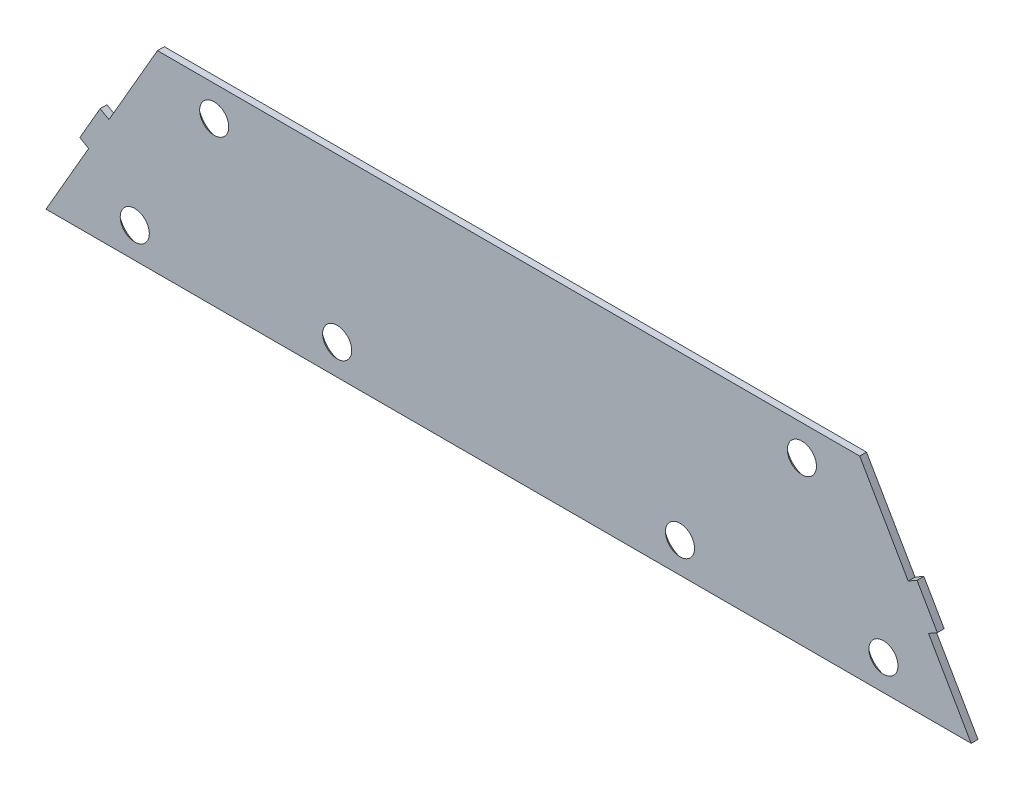
SolidWorks part; units mm, degrees
material "1023 Carbon Steel Sheet (SS)"
ref_plane "Front Plane" through (0, 0, 0) normal (0, 0, 1) x (1, 0, 0)
ref_plane "Top Plane" through (0, 0, 0) normal (0, 1, 0) x (1, 0, 0)
ref_plane "Right Plane" through (0, 0, 0) normal (1, 0, 0) x (0, 0, -1)
sketch "Sketch1" plane through (0, 0, 0) normal (0, 0, 1) x (1, 0, 0)
  line L0 (-55.1914, 13.7311) -> (-72.6057, -16.4314)
  line L1 (75.6033, -16.4314) -> (-72.6057, -16.4314)
  line L3 (58.189, 13.7311) -> (-55.1914, 13.7311)
  line L8 (58.189, 13.7311) -> (75.6033, -16.4314)
  point P0 (0, 0)
  dimension "D1" = 30.1625
  dimension "D2" = 148.209
  dimension "D3" = 60
  dimension "D4" = 60
extrude "Boss-Extrude1" add sketch "Sketch1" along normal blind 1.0668
ref_plane "Plane1" through (1.4988, 0, 0) normal (-1, 0, 0) x (0, 0, 1)
hole_wizard "CSK for #6 Flat Head Machine Screw (100)1" positions "Sketch3" profile "Sketch2" countersink size "#6" standard "ANSI Inch" end condition through all
sketch "Sketch3" plane through (0, 0, 0) normal (0, 0, -1) x (-1, 0, 0)
  circle A6 centre (-47.3288, 8.9686) radius 1.3525 construction
  circle A7 centre (-28.2788, -11.6689) radius 1.3525 construction
  circle A11 centre (44.4922, 8.9686) radius 1.3525 construction
  point P46 (-28.2788, -11.6689)
  point P55 (44.4922, 8.9686)
  point P61 (-47.3288, 8.9686)
  point P105 (-60.0628, -11.6689)
  point P111 (56.9042, -11.6689)
  point P118 (25.2812, -11.6689)
sketch "Sketch2" plane through (28.2788, -11.6689, 0) normal (1, 0, 0) x (0, 1, 0)
  line L0 (0, 0) -> (0, 1.0668)
  line L1 (0, 1.0668) -> (1.8986, 1.0668)
  line L2 (1.8986, 1.0668) -> (1.8986, 1.38)
  line L3 (1.8986, 1.38) -> (3.5433, 0)
  line L5 (3.5433, 0) -> (0, 0)
  line L6 (-1.8986, 1.38) -> (-3.5433, 0) construction
  line L11 (0, -6.35) -> (0, 107.95) construction
  dimension "Thru Hole Dia." = 3.7973
  dimension "Thru Hole Depth" = 1.0668
  dimension "Near C'Sink Dia." = 7.0866
  dimension "Near C'Sink Angle" = 100
sketch "Sketch4" plane through (0, 0, 0) normal (0, 0, -1) x (-1, 0, 0)
  line L0 (-75.6033, -16.4314) -> (-58.189, 13.7311) construction
  line L1 (-58.189, 13.7311) -> (55.1914, 13.7311) construction
  line L2 (72.6057, -16.4314) -> (-75.6033, -16.4314) construction
  line L4 (-65.3086, 1.3995) -> (-63.9338, 0.6057)
  line L5 (-58.189, 13.7311) -> (55.1914, 13.7311) construction
  line L6 (72.6057, -16.4314) -> (-75.6033, -16.4314) construction
  line L7 (-58.189, 13.7311) -> (55.1914, 13.7311) construction
  line L8 (-75.6033, -16.4314) -> (-58.189, 13.7311) construction
  line L9 (72.6057, -16.4314) -> (-75.6033, -16.4314) construction
  line L10 (-56.3559, 13.7311) -> (-58.189, 13.7311)
  line L11 (-56.3559, 13.7311) -> (-73.7702, -16.4314) construction
  line L12 (-58.189, 13.7311) -> (-65.3086, 1.3995)
  line L13 (-75.6033, -16.4314) -> (-58.189, 13.7311) construction
  line L14 (-63.9338, 0.6057) -> (-56.3559, 13.7311)
  line L15 (-63.9338, 0.6057) -> (-65.3086, 1.3995) construction
  line L16 (-65.3086, 1.3995) -> (-68.4836, -4.0998) construction
  line L17 (-68.4836, -4.0998) -> (-67.1088, -4.8936) construction
  line L18 (-67.1088, -4.8936) -> (-63.9338, 0.6057) construction
  line L19 (-66.8961, -1.3502) -> (-65.5213, -2.1439) construction
  line L20 (-68.4836, -4.0998) -> (-67.1088, -4.8936)
  line L21 (-67.1088, -4.8936) -> (-73.7702, -16.4314)
  line L22 (-73.7702, -16.4314) -> (-75.6033, -16.4314)
  line L23 (-75.6033, -16.4314) -> (-68.4836, -4.0998)
  line L24 (-68.4836, -4.0998) -> (-58.9851, -4.2071)
  point P16 (-65.5213, -2.1439)
  dimension "D1" = 1.5875
  dimension "D4" = 6.35
extrude "Cut-Extrude1" cut sketch "Sketch4" against normal through all
mirror "Mirror1" about plane through (1.4988, 0, 0) normal (-1, 0, 0) of "Cut-Extrude1"
